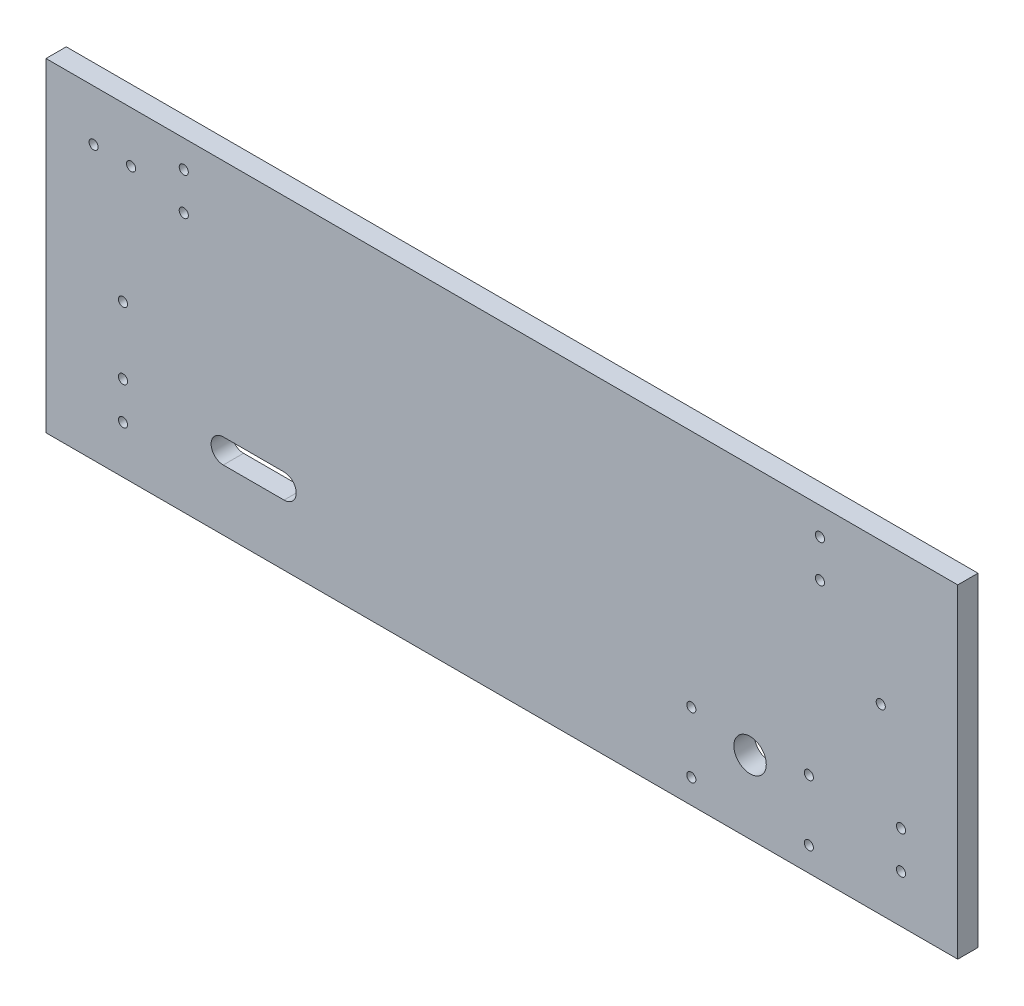
SolidWorks part; units mm, degrees
material "Pino"
ref_plane "Piano frontale" through (0, 0, 0) normal (0, 0, 1) x (1, 0, 0)
ref_plane "Piano superiore" through (0, 0, 0) normal (0, 1, 0) x (1, 0, 0)
ref_plane "Piano destro" through (0, 0, 0) normal (1, 0, 0) x (0, 0, -1)
sketch "Schizzo1" plane through (0, 0, 0) normal (0, 0, 1) x (1, 0, 0)
  line L1 (0, 0) -> (450, 0)
  line L2 (0, 0) -> (0, 160)
  line L3 (0, 160) -> (450, 160)
  line L4 (450, 0) -> (450, 160)
  dimension "D1" = 450
  dimension "D2" = 160
extrude "Estrusione-Estrusione1" add sketch "Schizzo1" along normal blind 10
sketch "Schizzo2" plane through (0, 0, 10) normal (0, 0, 1) x (1, 0, 0)
  line L0 (102.5, 36) -> (347.5, 36) construction
  line L1 (225, 0) -> (225, 36) construction
  line L2 (0, 0) -> (450, 0) construction
  line L3 (87.5, 36) -> (117.5, 36) construction
  line L4 (87.5, 42) -> (117.5, 42)
  line L5 (87.5, 30) -> (117.5, 30)
  line L7 (376.5, 42) -> (318.5, 42) construction
  line L8 (376.5, 42) -> (376.5, 12) construction
  line L9 (376.5, 12) -> (318.5, 12) construction
  line L10 (318.5, 42) -> (318.5, 12) construction
  circle A1 centre (347.5, 36) radius 8
  arc A2 (87.5, 42) -> (87.5, 30) centre (87.5, 36) ccw
  arc A3 (117.5, 30) -> (117.5, 42) centre (117.5, 36) ccw
  circle A4 centre (376.5, 42) radius 2.25
  circle A5 centre (318.5, 42) radius 2.25
  circle A6 centre (318.5, 12) radius 2.25
  circle A7 centre (376.5, 12) radius 2.25
  circle A8 centre (382, 146.5) radius 2.25
  circle A9 centre (382, 128) radius 2.25
  circle A10 centre (68, 146.5) radius 2.25
  circle A11 centre (68, 128) radius 2.25
  circle A12 centre (38, 42) radius 2.25
  circle A13 centre (38, 23.5) radius 2.25
  circle A14 centre (422, 23.5) radius 2.25
  circle A15 centre (422, 42) radius 2.25
  circle A16 centre (23.5, 134.9337) radius 2.25
  circle A17 centre (42, 134.9337) radius 2.25
  circle A18 centre (38, 75) radius 2.25
  circle A19 centre (412, 90) radius 2.25
  point P9 (102.5, 36)
  dimension "D2" = 16
  dimension "D3" = 12
  dimension "D5" = 30
  dimension "D6" = 29
  dimension "D7" = 6
  dimension "D8" = 4.5
  dimension "D10" = 29
  dimension "D20" = 4.5
  dimension "D11" = 4.5
  dimension "D1" = 36
  dimension "D4" = 245
  dimension "D9" = 30
extrude "Taglio-Estrusione1" cut sketch "Schizzo2" against normal blind 10
